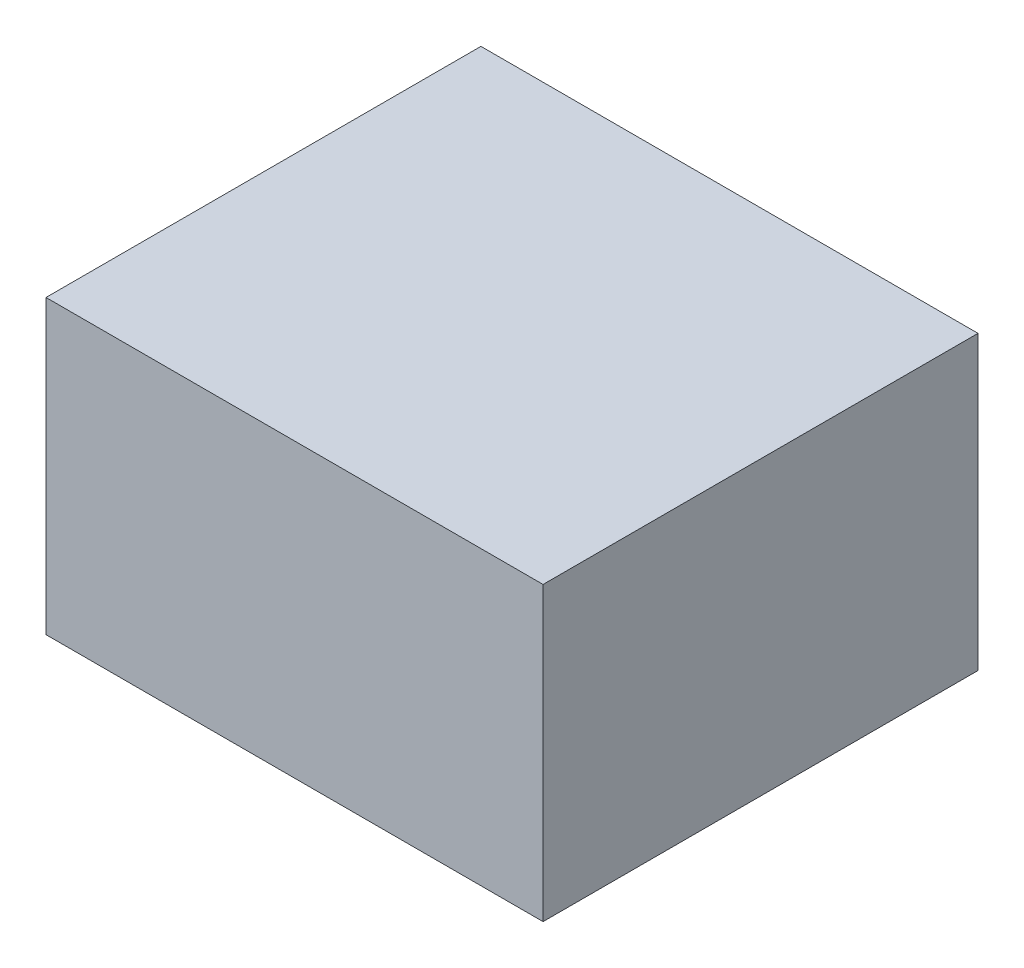
SolidWorks part; units mm, degrees
ref_plane "Plan de face" through (0, 0, 0) normal (0, 0, 1) x (1, 0, 0)
ref_plane "Plan de dessus" through (0, 0, 0) normal (0, 1, 0) x (1, 0, 0)
ref_plane "Plan de droite" through (0, 0, 0) normal (1, 0, 0) x (0, 0, -1)
sketch "Esquisse1" plane through (0, 0, 0) normal (0, 0, 1) x (1, 0, 0)
  line L1 (0, 0) -> (-8, 0)
  line L2 (0, 0) -> (0, 4.7)
  line L3 (0, 4.7) -> (-8, 4.7)
  line L4 (-8, 0) -> (-8, 4.7)
  dimension "D1" = 4.7
  dimension "D2" = 8
extrude "Boss.-Extru.1" add sketch "Esquisse1" along normal blind 7
